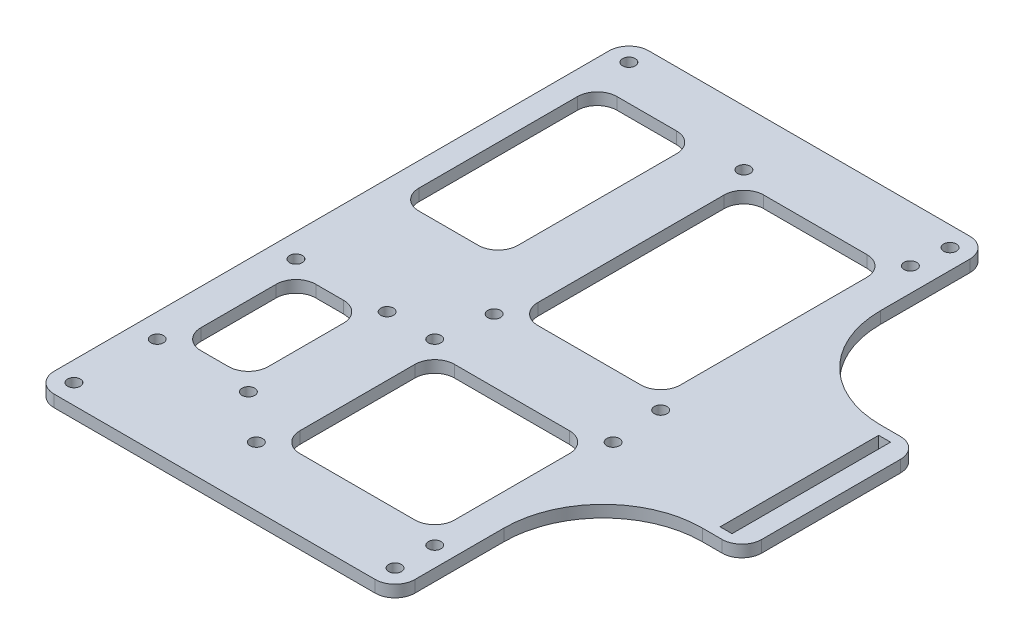
SolidWorks part; units mm, degrees
ref_plane "Front Plane" through (0, 0, 0) normal (0, 0, 1) x (1, 0, 0)
ref_plane "Top Plane" through (0, 0, 0) normal (0, 1, 0) x (1, 0, 0)
ref_plane "Right Plane" through (0, 0, 0) normal (1, 0, 0) x (0, 0, -1)
sketch "Sketch1" plane through (0, 0, 0) normal (0, 1, 0) x (1, 0, 0)
  line L1 (0, 0) -> (138, 0)
  line L2 (0, 0) -> (0, 170)
  line L3 (0, 170) -> (138, 170)
  line L4 (138, 0) -> (138, 170)
  dimension "D1" = 138
  dimension "D2" = 170
extrude "Boss-Extrude1" add sketch "Sketch1" along normal blind 3
sketch "Sketch2" plane through (0, 3, 0) normal (0, 1, 0) x (1, 0, 0)
  line L0 (0, 132) -> (138, 132) construction
  line L1 (0, 170) -> (29, 170)
  line L2 (0, 170) -> (0, 140)
  line L3 (0, 140) -> (29, 140)
  line L4 (29, 170) -> (29, 140)
  line L5 (138, 170) -> (109, 170)
  line L6 (138, 170) -> (138, 140)
  line L7 (138, 140) -> (109, 140)
  line L8 (109, 170) -> (109, 140)
  line L9 (138, 0) -> (109, 0)
  line L10 (138, 0) -> (138, 30)
  line L11 (138, 30) -> (109, 30)
  line L12 (109, 0) -> (109, 30)
  line L13 (0, 0) -> (29, 0)
  line L14 (0, 0) -> (0, 30)
  line L15 (0, 30) -> (29, 30)
  line L16 (29, 0) -> (29, 30)
  line L18 (0, 38) -> (138, 38) construction
  line L20 (29, 165) -> (109, 165) construction
  line L21 (29, 5) -> (109, 5) construction
  line L22 (69, 165) -> (69, 5) construction
  line L23 (138, 0) -> (138, 170) construction
  line L24 (69, 85) -> (138, 85) construction
  line L25 (0, 170) -> (0, 0) construction
  line L26 (10, 160) -> (10, 10)
  line L27 (10, 10) -> (128, 10)
  line L28 (128, 10) -> (128, 160)
  line L29 (128, 160) -> (10, 160)
  line L30 (10, 160) -> (10, 10) construction
  line L31 (10, 10) -> (128, 10) construction
  line L32 (128, 10) -> (128, 160) construction
  line L33 (128, 160) -> (10, 160) construction
  line L34 (138, 170) -> (0, 170) construction
  circle A220 centre (69, 165) radius 2.1
  circle A221 centre (69, 5) radius 2.1
  point P225 (69, 170)
  dimension "D12" = 4.2
  dimension "D13" = 4.2
  dimension "D1" = 30
  dimension "D2" = 160
  dimension "D5" = 8
  dimension "D9" = 30
  dimension "D10" = 80
  dimension "D11" = 8
  dimension "D3" = 10
extrude "Cut-Extrude1" cut sketch "Sketch2" against normal blind 3
sketch "Sketch3" plane through (0, 3, 0) normal (0, 1, 0) x (1, 0, 0)
  line L0 (69, 170) -> (69, 139.75) construction
  line L1 (14, 139.75) -> (124, 139.75) construction
  line L2 (14, 139.75) -> (14, 30.25) construction
  line L3 (14, 30.25) -> (124, 30.25) construction
  line L4 (124, 139.75) -> (124, 30.25) construction
  line L5 (109, 170) -> (29, 170) construction
  line L7 (14, 85) -> (0, 85) construction
  line L8 (0, 140) -> (0, 30) construction
  circle A0 centre (14, 125) radius 2.1
  circle A1 centre (14, 45) radius 2.1
  circle A2 centre (14, 85) radius 2.1
  circle A3 centre (124, 45) radius 2.1
  circle A5 centre (124, 125) radius 2.1
  point P23 (0, 0)
  dimension "D3" = 4.2
  dimension "D4" = 40
  dimension "D1" = 109.5
  dimension "D2" = 110
  dimension "D5" = 40
extrude "Cut-Extrude2" cut sketch "Sketch3" against normal through all
sketch "Sketch4" plane through (0, 0, 0) normal (0, 1, 0) x (1, 0, 0)
  line L0 (109, 170) -> (29, 170) construction
  line L1 (-2, 181) -> (140, 181)
  line L2 (-2, 181) -> (-2, -11)
  line L3 (-2, -11) -> (140, -11)
  line L4 (140, 181) -> (140, -11)
  line L6 (138, 30) -> (138, 140) construction
  point P6 (69, 170)
  point P7 (69, 181)
  point P12 (138, 85)
  point P13 (-2, 85)
  dimension "D1" = 192
  dimension "D2" = 142
sketch "Sketch5" plane through (0, 3, 0) normal (0, 1, 0) x (1, 0, 0)
  line L0 (29, 140) -> (29, 170) construction
  line L1 (0, 140) -> (29, 140)
  line L2 (0, 140) -> (0, 105)
  line L3 (0, 105) -> (29, 105)
  line L4 (29, 140) -> (29, 105)
  line L5 (0, 30) -> (29, 30)
  line L6 (0, 30) -> (0, 65)
  line L7 (0, 65) -> (29, 65)
  line L8 (29, 30) -> (29, 65)
  dimension "D1" = 35
extrude "Cut-Extrude3" cut sketch "Sketch5" against normal through all
sketch "Sketch6" plane through (0, 3, 0) normal (0, 1, 0) x (1, 0, 0)
  line L0 (138, 30) -> (138, 140) construction
  line L1 (130, 105) -> (133, 105)
  line L2 (130, 105) -> (130, 90)
  line L3 (130, 90) -> (133, 90)
  line L4 (133, 105) -> (133, 90)
  line L5 (109, 140) -> (138, 140) construction
  line L6 (0, 85) -> (138, 85) construction
  line L7 (0, 105) -> (0, 65) construction
  line L8 (130, 80) -> (133, 80)
  line L9 (133, 65) -> (133, 80)
  line L10 (130, 65) -> (133, 65)
  line L11 (130, 65) -> (130, 80)
  line L12 (131.5, 113) -> (131.5, 57) construction
  circle A0 centre (131.5, 113) radius 1.6
  circle A1 centre (131.5, 57) radius 1.6
  point P21 (131.5, 105)
  dimension "D5" = 3.2
  dimension "D6" = 8
  dimension "D1" = 5
  dimension "D2" = 3
  dimension "D3" = 35
  dimension "D4" = 15
  dimension "D7" = 8
extrude "Cut-Extrude4" cut sketch "Sketch6" against normal through all
sketch "Sketch9" plane through (0, 3, 0) normal (0, 1, 0) x (1, 0, 0)
  line L1 (109, 170) -> (138, 170)
  line L2 (109, 170) -> (109, 140)
  line L3 (109, 140) -> (138, 140)
  line L4 (138, 170) -> (138, 140)
  line L5 (109, 0) -> (138, 0)
  line L6 (109, 0) -> (109, 30)
  line L7 (109, 30) -> (138, 30)
  line L8 (138, 0) -> (138, 30)
extrude "Boss-Extrude2" add sketch "Sketch9" against normal up to surface (3 mm away) up to face at (131.5, 0, -55.4)
sketch "Sketch11" plane through (0, 3, 0) normal (0, 1, 0) x (1, 0, 0)
  line L0 (108, 85) -> (-2, 85) construction
  line L1 (108, 103.5) -> (130, 103.5)
  line L2 (108, 103.5) -> (108, 66.5)
  line L3 (108, 66.5) -> (130, 66.5)
  line L4 (130, 103.5) -> (130, 66.5)
  line L5 (-2, 181) -> (-2, -11) construction
  line L6 (130, 105) -> (130, 90) construction
  point P10 (0, 0)
  dimension "D1" = 22
  dimension "D2" = 37
sketch "Sketch15" plane through (0, 3, 0) normal (0, 1, 0) x (1, 0, 0)
  line L1 (29, 170) -> (0, 170)
  line L2 (29, 170) -> (29, 105)
  line L3 (29, 105) -> (0, 105)
  line L4 (0, 170) -> (0, 105)
  line L5 (0, 65) -> (29, 65)
  line L6 (0, 65) -> (0, 0)
  line L7 (0, 0) -> (29, 0)
  line L8 (29, 65) -> (29, 0)
extrude "Boss-Extrude3" add sketch "Sketch15" against normal up to surface (3 mm away) up to face at (49, 0, -85)
sketch "Sketch14" plane through (0, 3, 0) normal (0, 1, 0) x (1, 0, 0)
  line L0 (108, 85) -> (-2, 85) construction
  line L1 (13, 150) -> (103, 150) construction
  line L2 (13, 150) -> (13, 20) construction
  line L3 (13, 20) -> (103, 20) construction
  line L4 (103, 150) -> (103, 20) construction
  line L7 (18, 35) -> (41, 35) construction
  line L8 (18, 35) -> (18, 70) construction
  line L9 (18, 70) -> (41, 70) construction
  line L10 (41, 35) -> (41, 70) construction
  line L11 (53, 25) -> (98, 25) construction
  line L12 (53, 25) -> (53, 70) construction
  line L13 (53, 70) -> (98, 70) construction
  line L14 (98, 25) -> (98, 70) construction
  line L15 (55, 83) -> (97, 83) construction
  line L16 (55, 83) -> (55, 146) construction
  line L17 (55, 146) -> (97, 146) construction
  line L18 (97, 83) -> (97, 146) construction
  line L19 (18, 146) -> (43, 146)
  line L20 (18, 146) -> (18, 96)
  line L21 (18, 96) -> (43, 96)
  line L22 (43, 146) -> (43, 96)
  line L27 (138, 0) -> (138, 170) construction
  line L30 (58, 143) -> (94, 143)
  line L31 (94, 86) -> (94, 143)
  line L32 (58, 86) -> (94, 86)
  line L33 (58, 86) -> (58, 143)
  line L34 (56, 67) -> (95, 67)
  line L35 (95, 28) -> (95, 67)
  line L36 (56, 28) -> (95, 28)
  line L37 (56, 28) -> (56, 67)
  line L38 (38, 38) -> (38, 67)
  line L39 (21, 67) -> (38, 67)
  line L40 (21, 38) -> (21, 67)
  line L41 (21, 38) -> (38, 38)
  circle A0 centre (55, 146) radius 1.6
  circle A1 centre (97, 146) radius 1.6
  circle A2 centre (55, 83) radius 1.6
  circle A3 centre (97, 83) radius 1.6
  circle A4 centre (53, 70) radius 1.6
  circle A5 centre (98, 70) radius 1.6
  circle A6 centre (53, 25) radius 1.6
  circle A7 centre (98, 25) radius 1.6
  circle A8 centre (41, 70) radius 1.6
  circle A9 centre (18, 70) radius 1.6
  circle A10 centre (18, 35) radius 1.6
  circle A11 centre (41, 35) radius 1.6
  point P7 (13, 85)
  dimension "D15" = 3.2
  dimension "D1" = 130
  dimension "D2" = 90
  dimension "D3" = 35
  dimension "D4" = 42
  dimension "D5" = 63
  dimension "D6" = 45
  dimension "D7" = 45
  dimension "D8" = 13
  dimension "D9" = 35
  dimension "D10" = 23
  dimension "D11" = 5
  dimension "D12" = 12
  dimension "D13" = 6
  dimension "D14" = 5
  dimension "D16" = 50
  dimension "D17" = 25
  dimension "D18" = 3
extrude "Cut-Extrude8" cut sketch "Sketch14" against normal through all
sketch "Sketch16" plane through (0, 3, 0) normal (0, 1, 0) x (1, 0, 0)
  line L0 (0, 0) -> (138, 0) construction
  line L1 (138, 170) -> (103, 170)
  line L2 (138, 170) -> (138, 107.5)
  line L3 (138, 107.5) -> (103, 107.5)
  line L4 (103, 170) -> (103, 107.5)
  line L5 (138, 0) -> (103, 0)
  line L6 (138, 0) -> (138, 62.5)
  line L7 (138, 62.5) -> (103, 62.5)
  line L8 (103, 0) -> (103, 62.5)
  line L9 (0, 170) -> (12, 170)
  line L10 (0, 170) -> (0, 0)
  line L11 (0, 0) -> (12, 0)
  line L12 (12, 170) -> (12, 0)
  dimension "D1" = 45
  dimension "D2" = 35
  dimension "D3" = 12
extrude "Cut-Extrude9" cut sketch "Sketch16" against normal through all
sketch "Sketch17" plane through (0, 3, 0) normal (0, 1, 0) x (1, 0, 0)
  line L0 (130, 65) -> (133, 65) construction
  line L1 (130, 105) -> (133, 105)
  line L2 (130, 105) -> (130, 65)
  line L3 (130, 65) -> (133, 65)
  line L4 (133, 105) -> (133, 65)
  line L5 (133, 65) -> (133, 80) construction
  line L6 (103, 170) -> (103, 107.5) construction
  line L7 (12, 170) -> (103, 170)
  line L8 (12, 170) -> (12, 160)
  line L9 (12, 160) -> (103, 160)
  line L10 (103, 170) -> (103, 160)
  line L11 (103, 62.5) -> (103, 0) construction
  line L12 (12, 0) -> (103, 0)
  line L13 (12, 0) -> (12, 10)
  line L14 (12, 10) -> (103, 10)
  line L15 (103, 0) -> (103, 10)
  dimension "D1" = 10
extrude "Cut-Extrude10" cut sketch "Sketch17" against normal through all
sketch "Sketch18" plane through (0, 3, 0) normal (0, 1, 0) x (1, 0, 0)
  line L0 (12, 10) -> (12, 84.3597) construction
  line L1 (12, 90) -> (22, 90)
  line L2 (12, 90) -> (12, 80)
  line L3 (12, 80) -> (22, 80)
  line L4 (22, 90) -> (22, 80)
  line L5 (108, 85) -> (-2, 85) construction
  point P6 (22, 85)
  dimension "D1" = 10
  dimension "D2" = 10
extrude "Boss-Extrude4" add sketch "Sketch18" against normal up to surface (3 mm away) up to face at (131.5, 0, -85)
fillet "Fillet5" radius 5 6 edges at (138, 1.5, -107.5) (138, 1.5, -62.5) (103, 1.5, -10) (103, 1.5, -160) (12, 1.5, -160) (12, 1.5, -10)
fillet "Fillet6" radius 25 2 edges at (103, 1.5, -107.5) (103, 1.5, -62.5)
fillet "Fillet7" radius 5 4 edges at (43, 1.5, -96) (43, 1.5, -146) (18, 1.5, -146) (18, 1.5, -96)
sketch "Sketch20" plane through (0, 3, 0) normal (0, 1, 0) x (1, 0, 0)
  line L0 (17, 160) -> (98, 160) construction
  line L1 (12, 15) -> (12, 155) construction
  line L2 (103, 37.5) -> (103, 15) construction
  line L3 (98, 10) -> (17, 10) construction
  circle A0 centre (17, 155) radius 1.6
  circle A1 centre (98, 155) radius 1.6
  circle A2 centre (17, 15) radius 1.6
  circle A3 centre (98, 15) radius 1.6
  point P8 (0, 0)
  point P9 (0, 0)
  point P10 (0, 0)
  point P11 (0, 0)
  dimension "D1" = 5
  dimension "D2" = 5
  dimension "D3" = 5
  dimension "D4" = 5
  dimension "D5" = 3.2
extrude "Cut-Extrude11" cut sketch "Sketch20" against normal through all
fillet "Fillet8" radius 5 12 edges at (21, 1.5, -38) (38, 1.5, -67) (38, 1.5, -38) (21, 1.5, -67) (95, 1.5, -67) (95, 1.5, -28) (56, 1.5, -28) (56, 1.5, -67) (94, 1.5, -143) (94, 1.5, -86) (58, 1.5, -86) (58, 1.5, -143)
